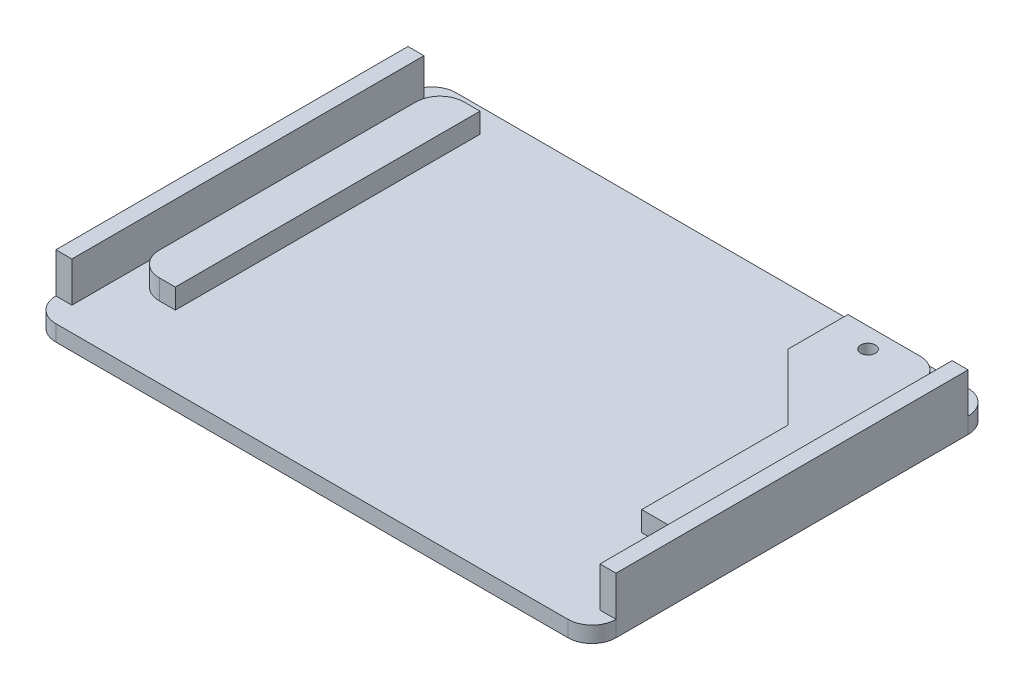
SolidWorks part; units mm, degrees
ref_plane "前视基准面" through (0, 0, 0) normal (0, 0, 1) x (1, 0, 0)
ref_plane "上视基准面" through (0, 0, 0) normal (0, 1, 0) x (1, 0, 0)
ref_plane "右视基准面" through (0, 0, 0) normal (1, 0, 0) x (0, 0, -1)
other "Configuration Table"
sketch "草图1" plane through (0, 0, 0) normal (0, 1, 0) x (1, 0, 0)
  line L1 (-35, 25) -> (35, 25)
  line L2 (-35, 25) -> (-35, -25)
  line L3 (-35, -25) -> (35, -25)
  line L4 (35, 25) -> (35, -25)
  line L5 (-35, 25) -> (35, -25) construction
  line L6 (-35, -25) -> (35, 25) construction
  point P0 (0, 0)
  dimension "D1" = 70
  dimension "D2" = 50
extrude "凸台-拉伸1" add sketch "草图1" along normal blind 2
fillet "圆角1" radius 3 4 edges at (-35, 1, 25) (35, 1, 25) (35, 1, -25) (-35, 1, -25)
sketch "草图2" plane through (0, 2, 0) normal (0, 1, 0) x (1, 0, 0)
  line L0 (0, 0) -> (0, 18.2368) construction
  line L1 (-35, 22) -> (-33, 22)
  line L2 (-35, 22) -> (-35, -22)
  line L3 (-35, -22) -> (-33, -22)
  line L4 (-33, 22) -> (-33, -22)
  line L5 (35, -22) -> (33, -22)
  line L6 (33, 22) -> (33, -22)
  line L7 (35, 22) -> (33, 22)
  line L8 (35, 22) -> (35, -22)
  dimension "D1" = 2
extrude "凸台-拉伸2" add sketch "草图2" along normal blind 5
sketch "草图3" plane through (0, 2, 0) normal (0, 1, 0) x (1, 0, 0)
  line L0 (33, 22) -> (33, -22) construction
  line L1 (28, 22.986) -> (19, 22.986)
  line L2 (31, 19.986) -> (31, -11.014)
  line L3 (31, -11.014) -> (27.2221, -11.014)
  line L4 (19, 22.986) -> (19, 15.466)
  line L5 (33, 22) -> (33, -22) construction
  line L6 (19, 15.466) -> (27.2221, 7.2439)
  line L7 (27.2221, 7.2439) -> (27.2221, -11.014)
  line L8 (-33, -22) -> (-33, 22) construction
  line L9 (-28, 22) -> (-26, 22)
  line L10 (-31, 19) -> (-31, -13.0718)
  line L11 (-28, -16.0718) -> (-26, -16.0718)
  line L12 (-26, 22) -> (-26, -16.0718)
  circle A0 centre (24, 20.4926) radius 0.91
  arc A1 (28, 22.986) -> (31, 19.986) centre (28, 19.986) cw
  arc A2 (-31, -13.0718) -> (-28, -16.0718) centre (-28, -13.0718) ccw
  arc A3 (-28, 22) -> (-31, 19) centre (-28, 19) ccw
  dimension "D3" = 9
  dimension "D5" = 3
  dimension "D6" = 2
  dimension "D8" = 3
  dimension "D1" = 2
  dimension "D2" = 34
  dimension "D4" = 12
  dimension "D7" = 5
extrude "凸台-拉伸3" add sketch "草图3" along normal blind 2.5
